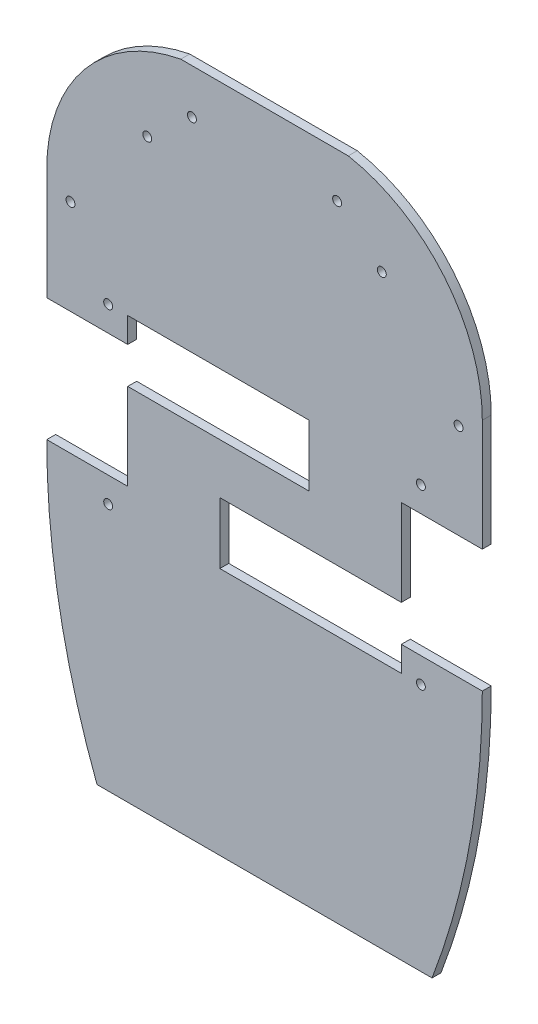
SolidWorks part; units mm, degrees
ref_plane "정면" through (0, 0, 0) normal (0, 0, 1) x (1, 0, 0)
ref_plane "윗면" through (0, 0, 0) normal (0, 1, 0) x (1, 0, 0)
ref_plane "우측면" through (0, 0, 0) normal (1, 0, 0) x (0, 0, -1)
sketch "스케치1" plane through (0, 0, 0) normal (0, 0, 1) x (1, 0, 0)
  line L0 (-12.1315, 60) -> (99.4316, 60) construction
  line L1 (39, 0) -> (9, 0)
  line L2 (39, 0) -> (69, 0)
  line L3 (39, 0) -> (39, 144.7704) construction
  line L4 (-44.7032, 0) -> (-44.7032, 85) construction
  line L5 (14.5, -11.5128) -> (14.5, 130.1512) construction
  line L6 (94.3796, 78) -> (94.3796, 42) construction
  line L7 (94.3796, 78) -> (-31.7708, 78) construction
  line L8 (63.5, -11.5128) -> (63.5, 132.0457) construction
  line L9 (94.3796, 42) -> (-31.7708, 42) construction
  line L10 (14.5, 130.1512) -> (16, 130.1512) construction
  line L11 (16, 130.1512) -> (16, -15.87) construction
  line L12 (63.5, 132.0457) -> (62, 132.0457) construction
  line L13 (62, 132.0457) -> (62, -19.5195) construction
  line L14 (62, 78) -> (67, 78) construction
  line L15 (67, 78) -> (67, 42) construction
  line L16 (53.183, 75.5) -> (72.1862, 75.5) construction
  line L17 (61.7506, 44.5) -> (75.7469, 44.5) construction
  line L18 (39, 120) -> (24, 120)
  line L19 (58.4094, 71) -> (86.2326, 71) construction
  line L20 (56.0147, 49) -> (84.2904, 49) construction
  line L21 (78, 71) -> (63.5, 71)
  line L22 (63.5, 71) -> (63.5, 55.5)
  line L23 (63.5, 49) -> (78, 49)
  line L24 (78, 91) -> (78, 71)
  line L25 (14.5, 49) -> (0, 49)
  line L26 (14.5, 64.5) -> (14.5, 49)
  line L27 (0, 71) -> (14.5, 71)
  line L28 (0, 91) -> (0, 71)
  line L29 (-10.0863, 78) -> (-10.0863, 75.5) construction
  line L30 (-10.0863, 75.5) -> (109.3331, 75.5) construction
  line L31 (-14.4537, 78) -> (-14.4537, 64.5) construction
  line L32 (-14.4537, 64.5) -> (109.3331, 64.5) construction
  line L33 (101.0087, 42) -> (101.0087, 44.5) construction
  line L34 (101.0087, 44.5) -> (-25.7071, 44.5) construction
  line L35 (-21.0824, 42) -> (-21.0824, 55.5) construction
  line L36 (-21.0824, 55.5) -> (107.175, 55.5) construction
  line L37 (39, 120) -> (54, 120)
  line L38 (14.5, 71) -> (14.5, 75.5)
  line L39 (14.5, 75.5) -> (47, 75.5)
  line L40 (47, 75.5) -> (47, 64.5)
  line L41 (47, 64.5) -> (14.5, 64.5)
  line L42 (63.5, 49) -> (63.5, 44.5) construction
  line L43 (-44.7032, 85) -> (124.8258, 85) construction
  line L44 (63.5, 49) -> (63.5, 44.5)
  line L45 (63.5, 44.5) -> (31, 44.5)
  line L46 (31, 44.5) -> (31, 55.5)
  line L47 (31, 55.5) -> (63.5, 55.5)
  line L48 (-19.4067, 85) -> (-19.4067, 88) construction
  line L49 (-19.4067, 88) -> (86.2326, 88) construction
  line L50 (0, 83.4505) -> (5, 83.4505) construction
  line L51 (5, 83.4505) -> (5, 97.0889) construction
  line L52 (73, 83.4505) -> (73, 97.0889) construction
  line L53 (5, 83.4505) -> (8, 83.4505) construction
  line L54 (8, 83.4505) -> (8, 116.8323) construction
  line L55 (73, 83.4505) -> (70, 83.4505) construction
  line L56 (70, 83.4505) -> (70, 116.8323) construction
  line L57 (-36.9729, 85) -> (-36.9729, 105) construction
  line L58 (-36.9729, 105) -> (109.3331, 105) construction
  line L59 (8, 114.4483) -> (18, 114.4483) construction
  line L60 (18, 114.4483) -> (18, 92.3941) construction
  line L61 (70, 115.3506) -> (60, 115.3506) construction
  line L62 (60, 115.3506) -> (60, 96.3037) construction
  line L63 (3.4548, 105) -> (3.4548, 112) construction
  line L64 (3.4548, 112) -> (84.2904, 112) construction
  line L65 (0, 127.1493) -> (26, 127.1493) construction
  line L66 (26, 127.1493) -> (26, 105.9194) construction
  line L67 (78, 122.3157) -> (52, 122.3157) construction
  line L68 (52, 122.3157) -> (52, 106.7724) construction
  line L69 (0, 86.1591) -> (4.25, 86.1591) construction
  line L70 (4.25, 86.1591) -> (4.25, 92.9389) construction
  line L71 (78, 86.1591) -> (73.75, 86.1591) construction
  line L72 (73.75, 86.1591) -> (73.75, 92.9389) construction
  circle A0 centre (67, 75.5) radius 0.8
  circle A1 centre (67, 44.5) radius 0.8
  circle A2 centre (11, 44.5) radius 0.8
  circle A3 centre (11, 75.5) radius 0.8
  arc A4 (0, 91) -> (24, 120) centre (29.5208, 91) cw
  arc A5 (78, 91) -> (54, 120) centre (48.4792, 91) ccw
  arc A6 (0, 49) -> (9, 0) centre (137.8889, 49) ccw
  arc A7 (78, 49) -> (69, 0) centre (-59.8889, 49) cw
  circle A8 centre (4.25, 88) radius 0.8
  circle A9 centre (73.75, 88) radius 0.8
  circle A10 centre (18, 105) radius 0.8
  circle A11 centre (60, 105) radius 0.8
  circle A12 centre (26, 112) radius 0.8
  circle A13 centre (52, 112) radius 0.8
  point P14 (94.3796, 60)
  dimension "D4" = 36
  dimension "D5" = 1.5
  dimension "D6" = 1.5
extrude "돌출1" add sketch "스케치1" along normal blind 1.6
